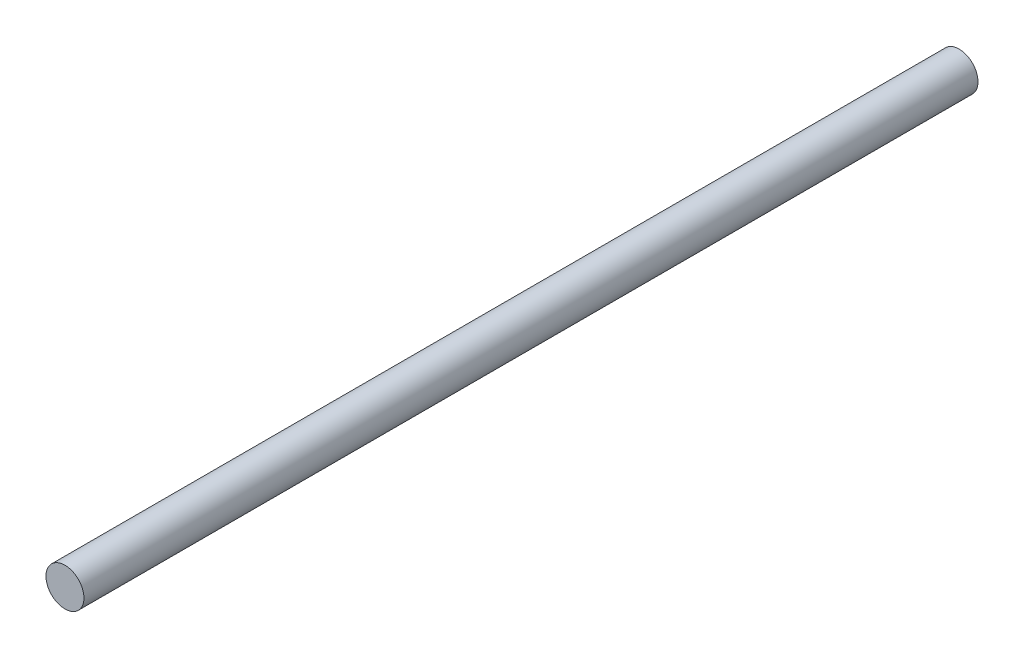
SolidWorks part; units mm, degrees
ref_plane "Alzado" through (0, 0, 0) normal (0, 0, 1) x (1, 0, 0)
ref_plane "Planta" through (0, 0, 0) normal (0, 1, 0) x (1, 0, 0)
ref_plane "Vista lateral" through (0, 0, 0) normal (1, 0, 0) x (0, 0, -1)
sketch "Croquis1" plane through (0, 0, 0) normal (0, 0, 1) x (1, 0, 0)
  circle A0 centre (0, 0) radius 1.25 construction
  circle A1 centre (0, 0) radius 1.25
extrude "Saliente-Extruir1" add sketch "Croquis1" against normal up to body (58.9 mm away) separate body
